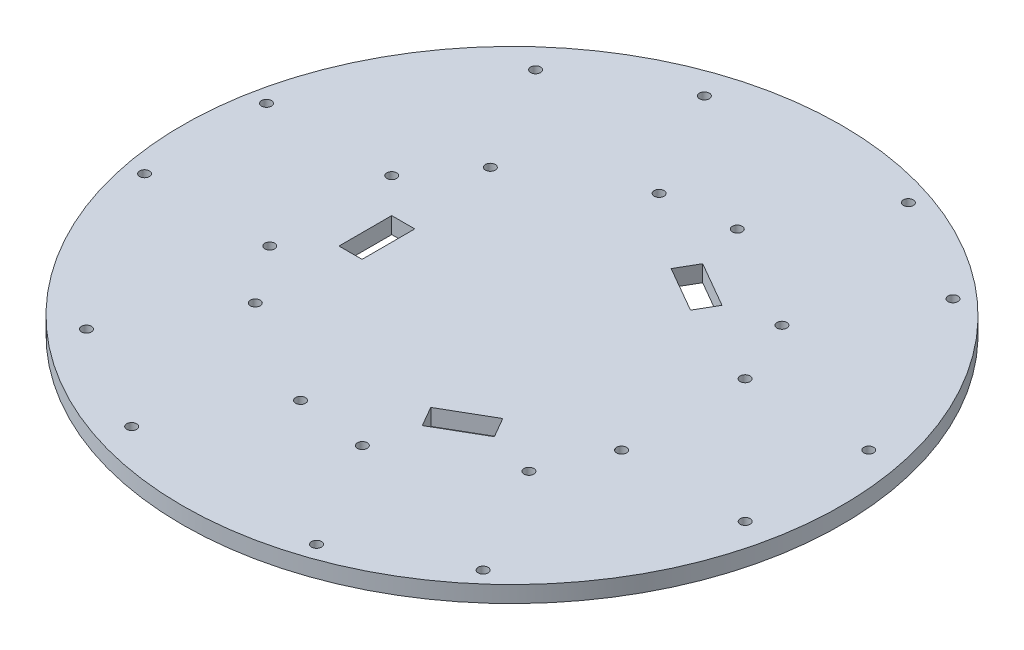
SolidWorks part; units mm, degrees
ref_plane "Plano frontal" through (0, 0, 0) normal (0, 0, 1) x (1, 0, 0)
ref_plane "Plano superior" through (0, 0, 0) normal (0, 1, 0) x (1, 0, 0)
ref_plane "Plano direito" through (0, 0, 0) normal (1, 0, 0) x (0, 0, -1)
sketch "Esboço1" plane through (0, 0, 0) normal (0, 1, 0) x (1, 0, 0)
  circle A0 centre (0, 0) radius 100
extrude "Ressalto-extrusão1" add sketch "Esboço1" along normal blind 5
sketch "Esboço2" plane through (0, 5, 0) normal (0, 1, 0) x (1, 0, 0)
  line L0 (-37.5, 0) -> (-37.5, 8)
  line L2 (-37.5, 8) -> (-44.5, 8)
  line L3 (-44.5, 8) -> (-44.5, -8)
  line L4 (-44.5, -8) -> (-37.5, -8)
  line L5 (-37.5, -8) -> (-37.5, 0)
  line L16 (18.75, -32.476) -> (11.8218, -36.476)
  line L18 (11.8218, -36.476) -> (15.3218, -42.5381)
  line L19 (15.3218, -42.5381) -> (29.1782, -34.5381)
  line L20 (29.1782, -34.5381) -> (25.6782, -28.476)
  line L21 (25.6782, -28.476) -> (18.75, -32.476)
  line L32 (18.75, 32.476) -> (25.6782, 28.476)
  line L34 (25.6782, 28.476) -> (29.1782, 34.5381)
  line L35 (29.1782, 34.5381) -> (15.3218, 42.5381)
  line L36 (15.3218, 42.5381) -> (11.8218, 36.476)
  line L37 (11.8218, 36.476) -> (18.75, 32.476)
  circle A1 centre (-93, 18.5) radius 1.5
  circle A2 centre (-55, 18.5) radius 1.5
  circle A3 centre (-55, -18.5) radius 1.5
  circle A4 centre (-93, -18.5) radius 1.5
  circle A5 centre (52, 18.75) radius 1.5
  circle A6 centre (89.5, 18.75) radius 1.5
  circle A7 centre (52, -18.75) radius 1.5
  circle A8 centre (89.5, -18.75) radius 1.5
  circle A9 centre (30.4785, -89.7904) radius 1.5
  circle A10 centre (11.4785, -56.8814) radius 1.5
  circle A11 centre (43.5215, -38.3814) radius 1.5
  circle A12 centre (62.5215, -71.2904) radius 1.5
  circle A13 centre (-42.238, 35.6583) radius 1.5
  circle A14 centre (-60.988, 68.1343) radius 1.5
  circle A15 centre (-9.762, 54.4083) radius 1.5
  circle A16 centre (-28.512, 86.8843) radius 1.5
  circle A17 centre (62.5215, 71.2904) radius 1.5
  circle A18 centre (43.5215, 38.3814) radius 1.5
  circle A19 centre (11.4785, 56.8814) radius 1.5
  circle A20 centre (30.4785, 89.7904) radius 1.5
  circle A21 centre (-9.762, -54.4083) radius 1.5
  circle A22 centre (-28.512, -86.8843) radius 1.5
  circle A23 centre (-42.238, -35.6583) radius 1.5
  circle A24 centre (-60.988, -68.1343) radius 1.5
extrude "Corte-extrusão1" cut sketch "Esboço2" against normal through all
